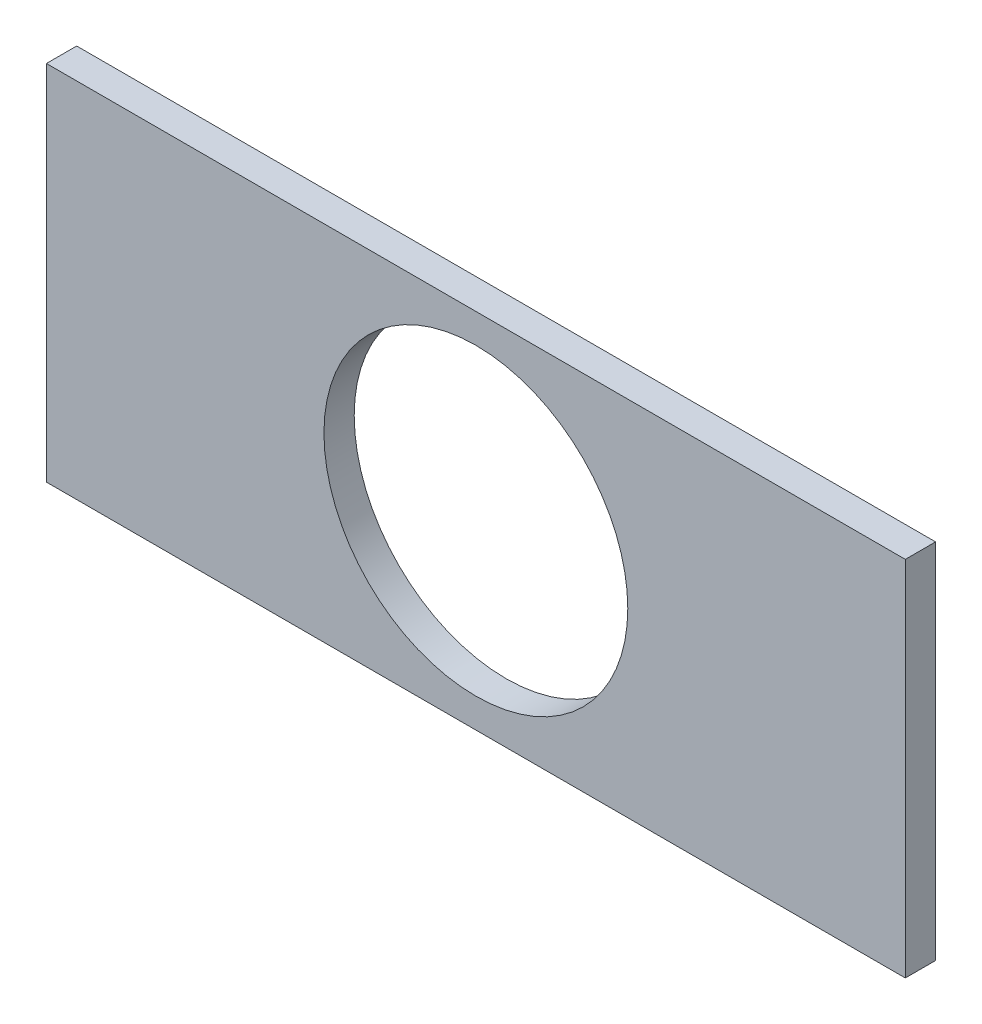
SolidWorks part; units mm, degrees
ref_plane "Front Plane" through (0, 0, 0) normal (0, 0, 1) x (1, 0, 0)
ref_plane "Top Plane" through (0, 0, 0) normal (0, 1, 0) x (1, 0, 0)
ref_plane "Right Plane" through (0, 0, 0) normal (1, 0, 0) x (0, 0, -1)
sketch "Sketch1" plane through (0, 0, 0) normal (0, 0, 1) x (1, 0, 0)
  line L1 (0, 0) -> (180.213, 0)
  line L2 (0, 0) -> (0, 76.073)
  line L3 (0, 76.073) -> (180.213, 76.073)
  line L4 (180.213, 0) -> (180.213, 76.073)
  dimension "D1" = 76.073
  dimension "D2" = 180.213
extrude "Boss-Extrude1" add sketch "Sketch1" along normal blind 6.35
sketch "Sketch3" plane through (0, 0, 6.35) normal (0, 0, 1) x (1, 0, 0)
  line L0 (0, 38.0365) -> (180.213, 38.0365) construction
  line L1 (0, 76.073) -> (0, 0) construction
  line L2 (180.213, 0) -> (180.213, 76.073) construction
  line L4 (180.213, 76.073) -> (0, 76.073) construction
  line L5 (90.1065, 76.073) -> (90.1065, 0) construction
  line L6 (0, 0) -> (180.213, 0) construction
sketch "Sketch4" plane through (0, 0, 6.35) normal (0, 0, 1) x (1, 0, 0)
  line L0 (0, 38.0365) -> (180.213, 38.0365) construction
  circle A0 centre (90.1065, 38.0365) radius 31.877
extrude "Cut-Extrude1" cut sketch "Sketch4" against normal through all
